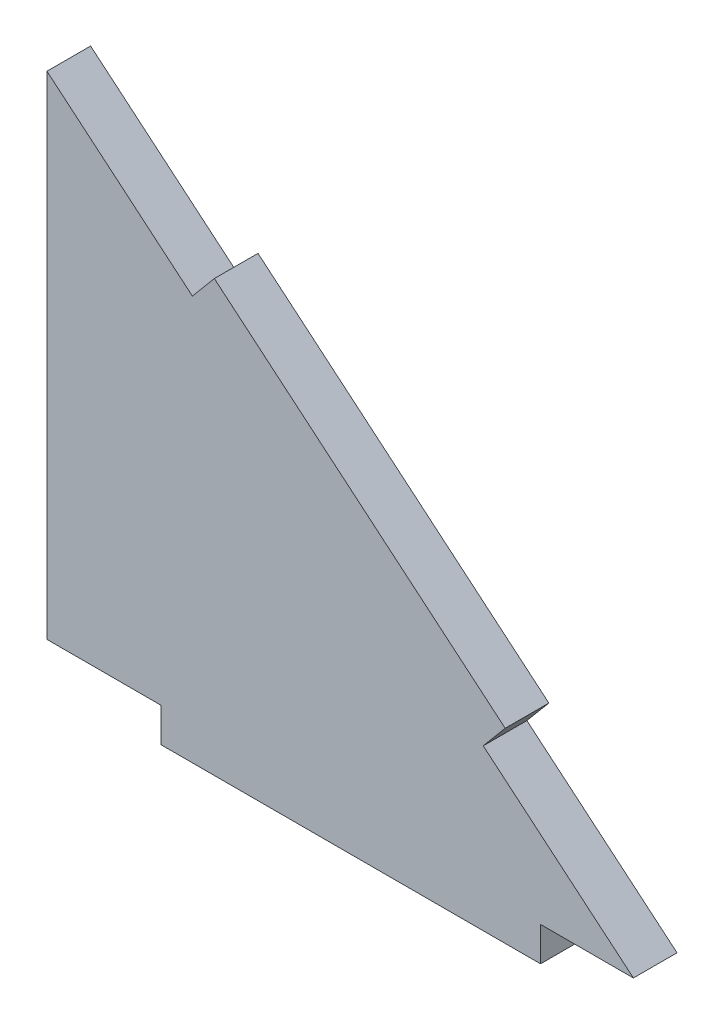
SolidWorks part; units mm, degrees
ref_plane "前视基准面" through (0, 0, 0) normal (0, 0, 1) x (1, 0, 0)
ref_plane "上视基准面" through (0, 0, 0) normal (0, 1, 0) x (1, 0, 0)
ref_plane "右视基准面" through (0, 0, 0) normal (1, 0, 0) x (0, 0, -1)
other "Configuration Table"
sketch "草图1" plane through (0, 0, 0) normal (0, 0, 1) x (1, 0, 0)
  line L2 (-23.0204, 5.056) -> (-23.0204, 8.656)
  line L3 (16.9796, 5.056) -> (16.9796, 8.656)
  line L4 (-23.0204, 8.656) -> (-35.0204, 8.656)
  line L6 (-35.0204, 8.656) -> (-35.0204, 60.4969)
  line L7 (-35.0204, 60.4969) -> (-19.6995, 47.6411)
  line L10 (-19.6995, 47.6411) -> (-17.3855, 50.3989)
  line L11 (-17.3855, 50.3989) -> (13.2563, 24.6874)
  line L12 (13.2563, 24.6874) -> (10.9422, 21.9296)
  line L15 (-23.0204, 5.056) -> (16.9796, 5.056)
  line L16 (24.8387, 10.2691) -> (10.9422, 21.9296)
  line L17 (24.8387, 10.2691) -> (25.7025, 9.5442)
  line L19 (16.9796, 8.656) -> (26.7611, 8.656)
  line L20 (26.7611, 8.656) -> (25.7025, 9.5442)
  point P4 (0, 0)
  dimension "D1" = 40
  dimension "D3" = 12
  dimension "D4" = 90
  dimension "D5" = 40
  dimension "D6" = 3.6
  dimension "D7" = 3.6
  dimension "D8" = 90
  dimension "D9" = 20.65
  dimension "D10" = 90
  dimension "D11" = 90
  dimension "D12" = 90
  dimension "D13" = 90
  dimension "D14" = 3.6
  dimension "D15" = 40
  dimension "D16" = 3.6
  dimension "D17" = 90
  dimension "D18" = 90
  dimension "D19" = 20
  dimension "D20" = 90
  dimension "D21" = 40
  dimension "D22" = 9.7815
extrude "凸台-拉伸1" add sketch "草图1" along normal blind 4.6
